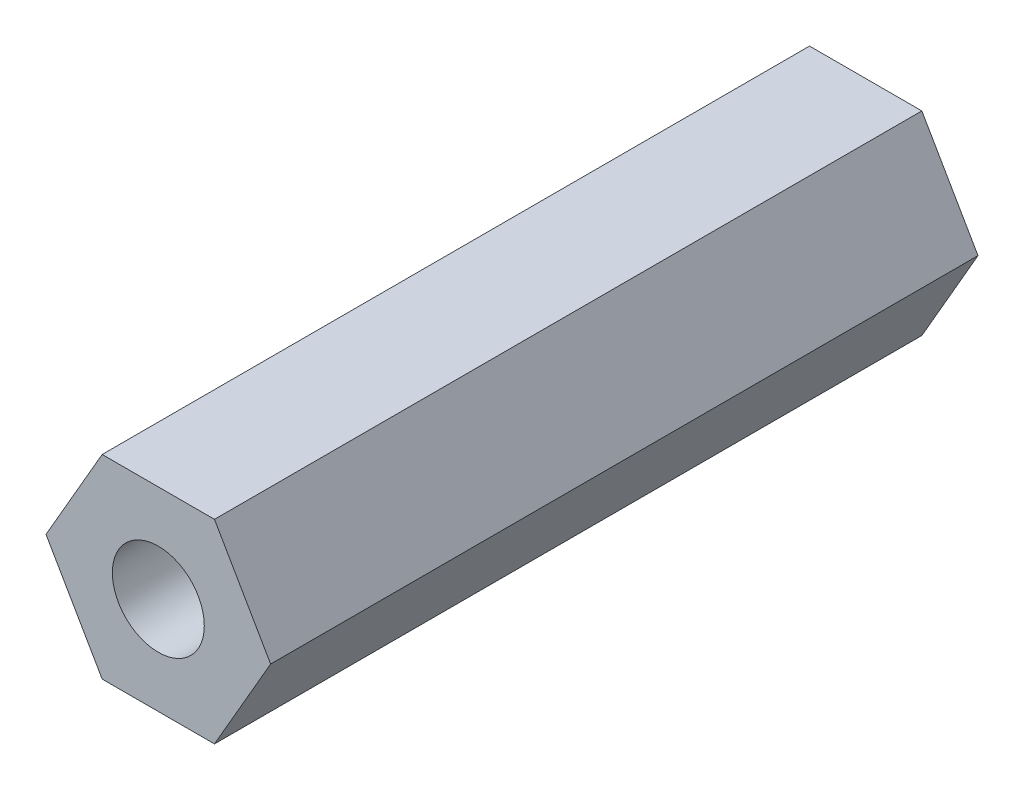
SolidWorks part; units mm, degrees
ref_plane "前视基准面" through (0, 0, 0) normal (0, 0, 1) x (1, 0, 0)
ref_plane "上视基准面" through (0, 0, 0) normal (0, 1, 0) x (1, 0, 0)
ref_plane "右视基准面" through (0, 0, 0) normal (1, 0, 0) x (0, 0, -1)
sketch "草图1" plane through (0, 0, 0) normal (0, 0, 1) x (1, 0, 0)
  line L1 (1.5877, 2.75) -> (-1.5877, 2.75)
  line L2 (-1.5877, 2.75) -> (-3.1754, 0)
  line L3 (-3.1754, 0) -> (-1.5877, -2.75)
  line L4 (-1.5877, -2.75) -> (1.5877, -2.75)
  line L5 (1.5877, -2.75) -> (3.1754, 0)
  line L6 (3.1754, 0) -> (1.5877, 2.75)
  circle A0 centre (0, 0) radius 2.75 construction
  circle A1 centre (0, 0) radius 1.3
  dimension "D1" = 5.5
  dimension "D2" = 2.6
extrude "凸台-拉伸1" add sketch "草图1" along normal blind 20
